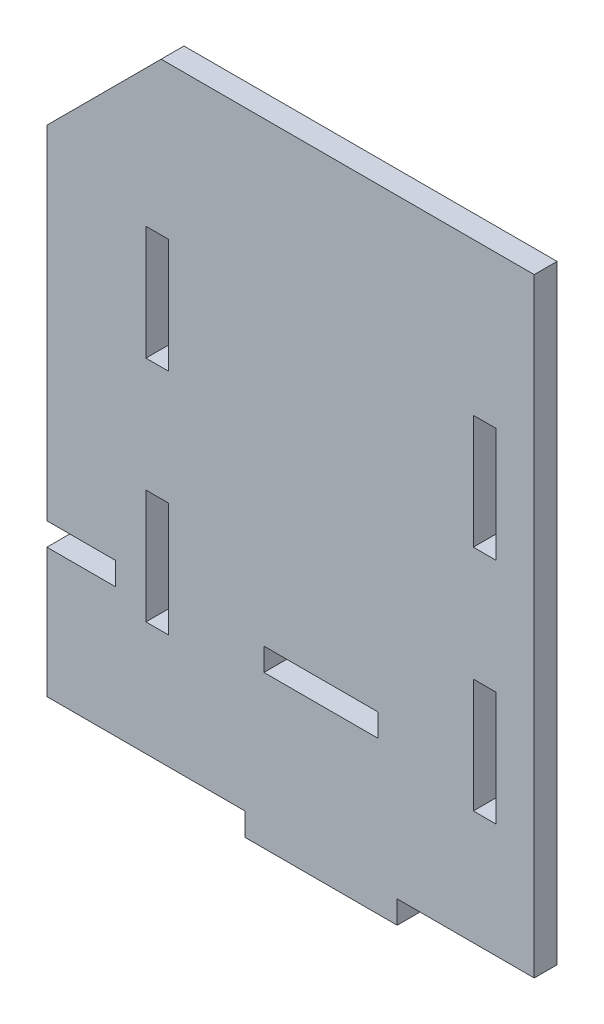
SolidWorks part; units mm, degrees
ref_plane "前视基准面" through (0, 0, 0) normal (0, 0, 1) x (1, 0, 0)
ref_plane "上视基准面" through (0, 0, 0) normal (0, 1, 0) x (1, 0, 0)
ref_plane "右视基准面" through (0, 0, 0) normal (1, 0, 0) x (0, 0, -1)
other "Configuration Table"
sketch "草图1" plane through (0, 0, 0) normal (0, 0, 1) x (1, 0, 0)
  line L0 (20, 20) -> (20, 5)
  line L1 (-28, 40) -> (28, 40)
  line L2 (-28, 40) -> (-28, -40)
  line L3 (-28, -40) -> (28, -40)
  line L4 (28, 40) -> (28, -40)
  line L5 (-28, 40) -> (28, -40) construction
  line L6 (-28, -40) -> (28, 40) construction
  line L7 (20, -10) -> (23, -10)
  line L8 (20, -10) -> (20, -25)
  line L9 (20, -25) -> (23, -25)
  line L10 (23, -10) -> (23, -25)
  line L11 (20, 20) -> (23, 20)
  line L12 (23, 20) -> (23, 5)
  line L13 (20, 5) -> (23, 5)
  line L14 (0, -11.8626) -> (0, 11.0284) construction
  line L15 (-20, -25) -> (-23, -25)
  line L16 (-23, -10) -> (-23, -25)
  line L17 (-20, -10) -> (-23, -10)
  line L18 (-20, -10) -> (-20, -25)
  line L19 (-20, 20) -> (-23, 20)
  line L20 (-23, 20) -> (-23, 5)
  line L21 (-20, 5) -> (-23, 5)
  line L22 (-20, 20) -> (-20, 5)
  line L24 (-10, -40) -> (10, -40)
  line L25 (-10, -40) -> (-10, -43)
  line L26 (-10, -43) -> (10, -43)
  line L27 (10, -40) -> (10, -43)
  point P0 (0, 0)
  point P28 (0, -43)
  dimension "D1" = 80
  dimension "D2" = 3
  dimension "D3" = 15
  dimension "D4" = 15
  dimension "D5" = 5
  dimension "D7" = 15
  dimension "D8" = 40
  dimension "D9" = 20
  dimension "D6" = 2
extrude "凸台-拉伸1" add sketch "草图1" along normal blind 3 contours L4 L1 L2 L3 L13 L0 L11 L12 L7 L10 L9 L8 L17 L18 L15 L16 L19 L22 L21 L20 | L26 L27 L24 L25
sketch "草图2" plane through (0, 0, 3) normal (0, 0, 1) x (1, 0, 0)
  line L1 (-7.5, -20) -> (7.5, -20)
  line L2 (-7.5, -20) -> (-7.5, -23)
  line L3 (-7.5, -23) -> (7.5, -23)
  line L4 (7.5, -20) -> (7.5, -23)
  point P4 (0, -20)
  dimension "D1" = 3
  dimension "D2" = 15
  dimension "D3" = 20
extrude "切除-拉伸1" cut sketch "草图2" against normal blind 3
sketch "草图3" plane through (0, 0, 3) normal (0, 0, 1) x (1, 0, 0)
  line L1 (-28, -40) -> (-36, -40)
  line L2 (-28, -40) -> (-28, 40)
  line L3 (-28, 40) -> (-36, 40)
  line L4 (-36, -40) -> (-36, 40)
  dimension "D1" = 8
extrude "凸台-拉伸2" add sketch "草图3" against normal blind 3
sketch "草图4" plane through (0, 0, 3) normal (0, 0, 1) x (1, 0, 0)
  line L0 (-36, 40) -> (-36, -40) construction
  line L1 (-36, -23) -> (-27, -23)
  line L2 (-36, -23) -> (-36, -20)
  line L3 (-36, -20) -> (-27, -20)
  line L4 (-27, -23) -> (-27, -20)
  line L5 (-7.5, -20) -> (-7.5, -23) construction
  line L6 (-7.5, -23) -> (7.5, -23) construction
  dimension "D1" = 9
extrude "切除-拉伸2" cut sketch "草图4" against normal blind 3
chamfer "倒角1" distance 15 angle 45 1 edges at (-36, 40, 1.5)
